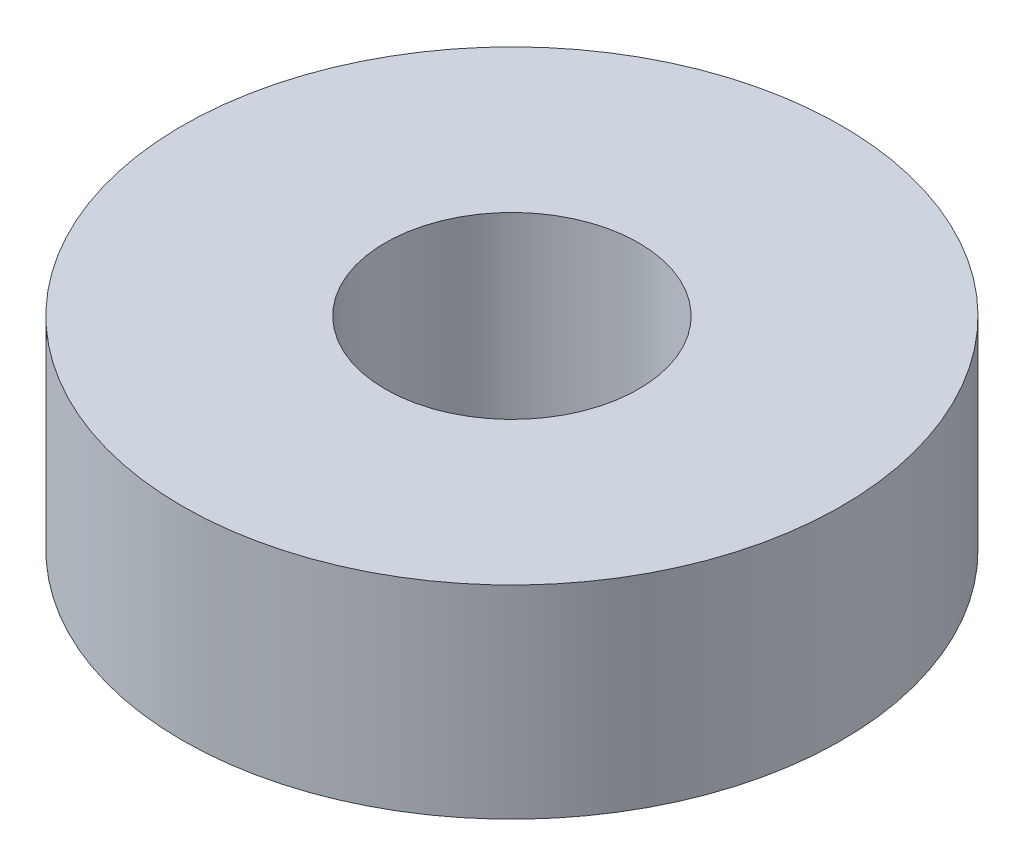
SolidWorks part; units mm, degrees
ref_plane "Front Plane" through (0, 0, 0) normal (0, 0, 1) x (1, 0, 0)
ref_plane "Top Plane" through (0, 0, 0) normal (0, 1, 0) x (1, 0, 0)
ref_plane "Right Plane" through (0, 0, 0) normal (1, 0, 0) x (0, 0, -1)
sketch "Sketch1" plane through (0, 0, 0) normal (0, 1, 0) x (1, 0, 0)
  circle A0 centre (0, 0) radius 6.5
  circle A1 centre (0, 0) radius 2.5
  dimension "D1" = 5
  dimension "D2" = 13
extrude "Boss-Extrude1" add sketch "Sketch1" along normal blind 4
